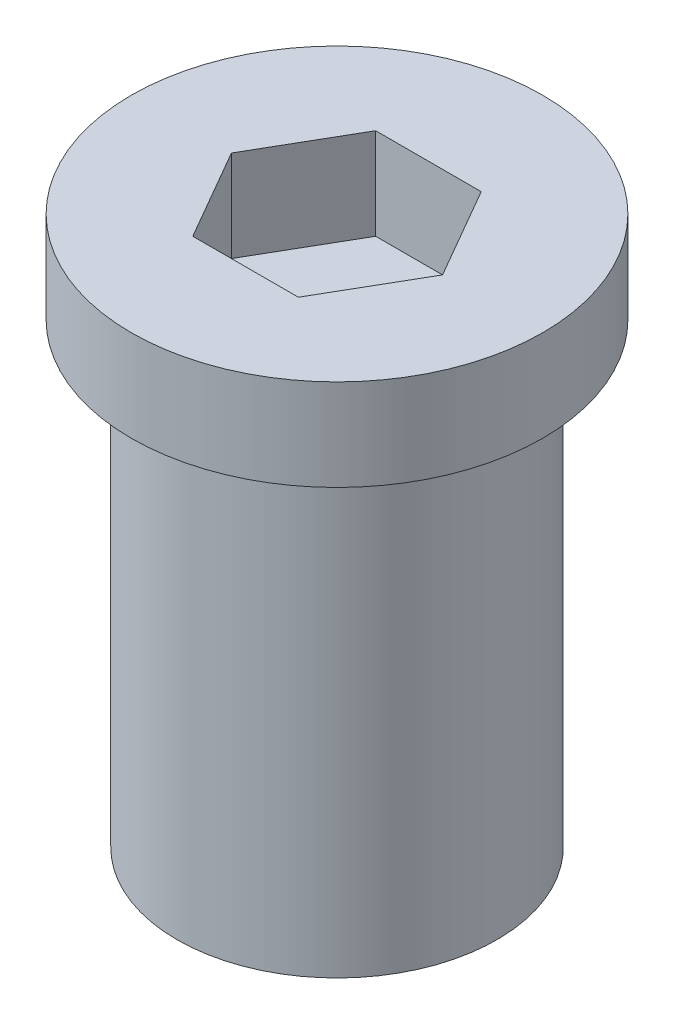
SolidWorks part; units mm, degrees
material "AISI 304"
ref_plane "Front Plane" through (0, 0, 0) normal (0, 0, 1) x (1, 0, 0)
ref_plane "Top Plane" through (0, 0, 0) normal (0, 1, 0) x (1, 0, 0)
ref_plane "Right Plane" through (0, 0, 0) normal (1, 0, 0) x (0, 0, -1)
sketch "Sketch1" plane through (0, 0, 0) normal (0, 1, 0) x (1, 0, 0)
  circle A0 centre (0, 0) radius 1.75
  dimension "D1" = 3.5
extrude "Boss-Extrude1" add sketch "Sketch1" along normal mid plane 5
sketch "Sketch2" plane through (0, 2.5, 0) normal (0, 1, 0) x (1, 0, 0)
  circle A0 centre (0, 0) radius 2.25
  dimension "D1" = 4.5
extrude "Boss-Extrude2" add sketch "Sketch2" along normal blind 1
sketch "Sketch3" plane through (0, 3.5, 0) normal (0, 1, 0) x (1, 0, 0)
  line L0 (1.1547, 0) -> (0.5774, 1)
  line L1 (0.5774, 1) -> (-0.5774, 1)
  line L2 (-0.5774, 1) -> (-1.1547, 0)
  line L3 (-1.1547, 0) -> (-0.5774, -1)
  line L4 (-0.5774, -1) -> (0.5774, -1)
  line L5 (0.5774, -1) -> (1.1547, 0)
  circle A0 centre (0, 0) radius 1 construction
  dimension "D1" = 1.1547
  dimension "D2" = 1.1547
  dimension "D3" = 1.1547
  dimension "D4" = 1.1547
  dimension "D5" = 1.1547
  dimension "D6" = 2.3094
extrude "Cut-Extrude1" cut sketch "Sketch3" against normal blind 1 contours L0 L1 L2 L3 L4 L5
